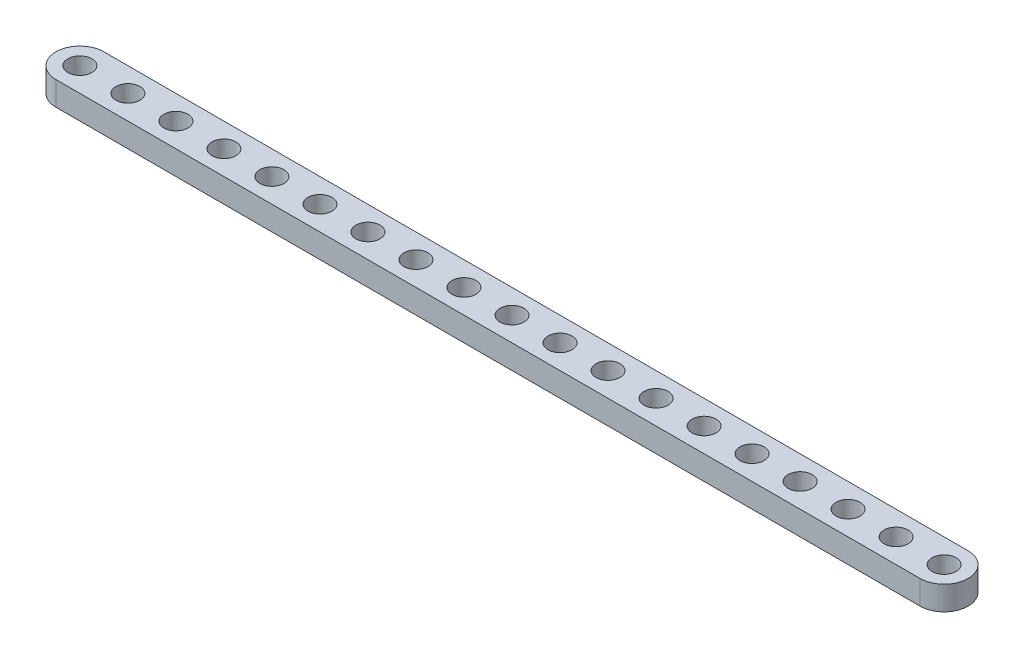
SolidWorks part; units mm, degrees
ref_plane "Front" through (0, 0, 0) normal (0, 0, 1) x (1, 0, 0)
ref_plane "Top" through (0, 0, 0) normal (0, 1, 0) x (1, 0, 0)
ref_plane "Right" through (0, 0, 0) normal (1, 0, 0) x (0, 0, -1)
ref_plane "Plane1" through (0, 0, 0) normal (0, -1, 0) x (1, 0, 0)
sketch "Sketch1" plane through (0, 0, 0) normal (0, -1, 0) x (1, 0, 0)
  line L0 (-72, -4) -> (72, -4)
  line L1 (72, 4) -> (-72, 4)
  arc A0 (72, -4) -> (72, 4) centre (72, 0) ccw
  arc A1 (-72, 4) -> (-72, -4) centre (-72, 0) ccw
  circle A2 centre (-72, 0) radius 2
  circle A3 centre (-64, 0) radius 2
  circle A4 centre (-56, 0) radius 2
  circle A5 centre (-48, 0) radius 2
  circle A6 centre (-40, 0) radius 2
  circle A7 centre (-32, 0) radius 2
  circle A8 centre (-24, 0) radius 2
  circle A9 centre (-16, 0) radius 2
  circle A10 centre (-8, 0) radius 2
  circle A11 centre (0, 0) radius 2
  circle A12 centre (8, 0) radius 2
  circle A13 centre (16, 0) radius 2
  circle A14 centre (24, 0) radius 2
  circle A15 centre (32, 0) radius 2
  circle A16 centre (40, 0) radius 2
  circle A17 centre (48, 0) radius 2
  circle A18 centre (56, 0) radius 2
  circle A19 centre (64, 0) radius 2
  circle A20 centre (72, 0) radius 2
extrude "Boss-Extrude1" add sketch "Sketch1" against normal blind 4
